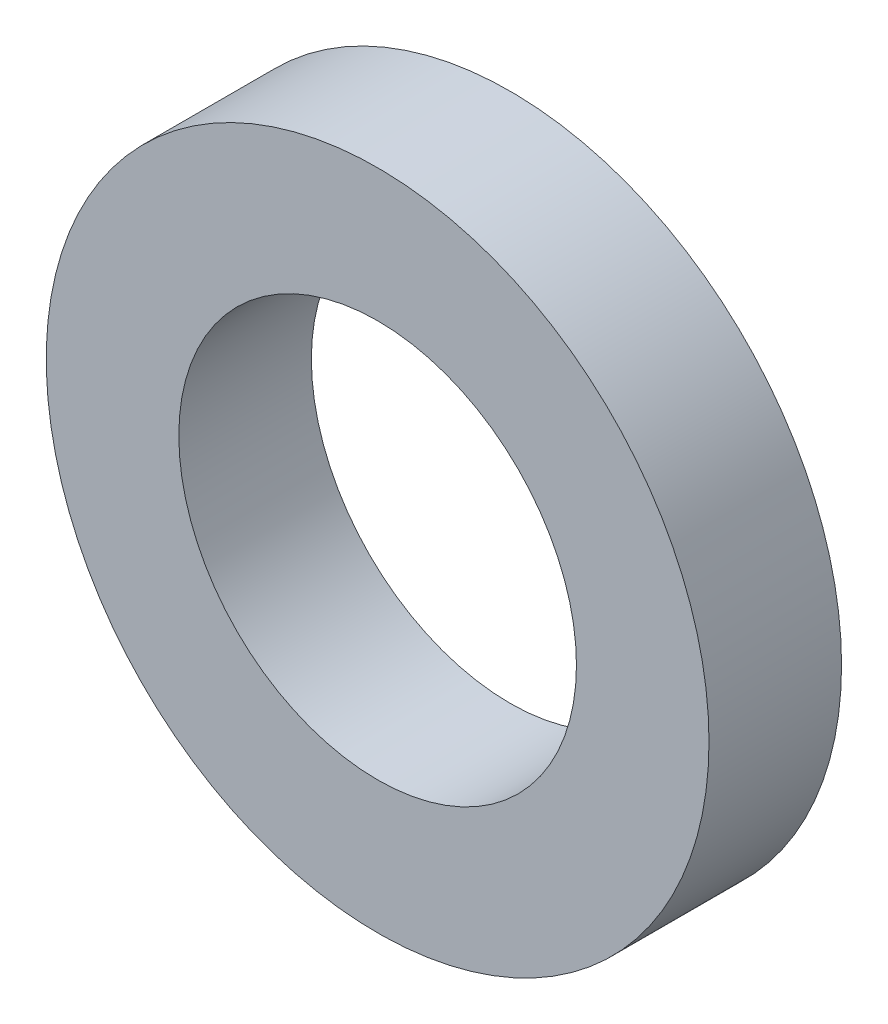
SolidWorks part; units mm, degrees
material "ABS"
ref_plane "Front Plane" through (0, 0, 0) normal (0, 0, 1) x (1, 0, 0)
ref_plane "Top Plane" through (0, 0, 0) normal (0, 1, 0) x (1, 0, 0)
ref_plane "Right Plane" through (0, 0, 0) normal (1, 0, 0) x (0, 0, -1)
sketch "Sketch1" plane through (0, 0, 0) normal (0, 0, 1) x (1, 0, 0)
  circle A0 centre (0, 0) radius 4.5
  circle A1 centre (0, 0) radius 7.5
  dimension "D1" = 15
  dimension "D2" = 9
extrude "Boss-Extrude1" add sketch "Sketch1" along normal blind 3
